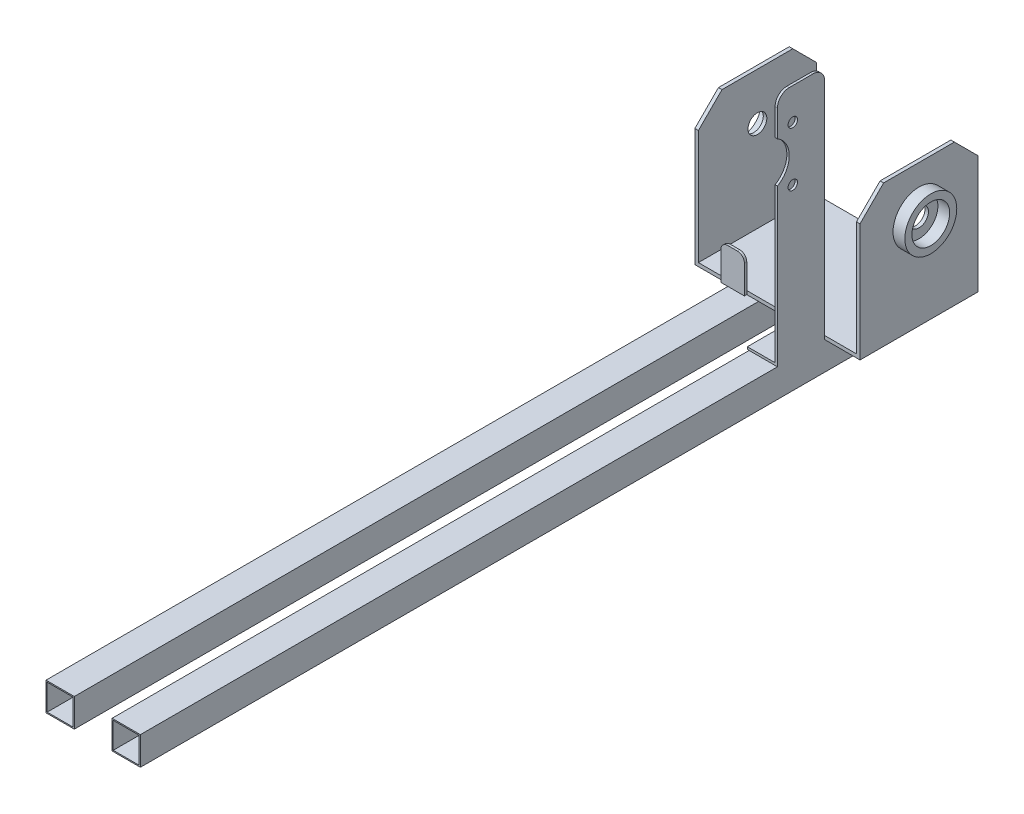
SolidWorks part; units mm, degrees
ref_plane "Front Plane" through (0, 0, 0) normal (0, 0, 1) x (1, 0, 0)
ref_plane "Top Plane" through (0, 0, 0) normal (0, 1, 0) x (1, 0, 0)
ref_plane "Right Plane" through (0, 0, 0) normal (1, 0, 0) x (0, 0, -1)
sketch "Sketch1" plane through (0, 0, 0) normal (0, 0, 1) x (1, 0, 0)
  line L0 (-65.8165, 13.0444) -> (-65.8165, -46.9556)
  line L1 (-65.8165, -46.9556) -> (4.1835, -46.9556)
  line L2 (4.1835, -46.9556) -> (4.1835, 13.0444)
  line L3 (-64.3165, 13.0444) -> (-64.3165, -45.4556)
  line L4 (-64.3165, -45.4556) -> (2.6835, -45.4556)
  line L5 (2.6835, -45.4556) -> (2.6835, 13.0444)
  line L6 (-65.8165, 13.0444) -> (-64.3165, 13.0444)
  line L8 (2.6835, 13.0444) -> (4.1835, 13.0444)
  dimension "D1" = 60
  dimension "D2" = 60
  dimension "D3" = 70
  dimension "D4" = 1.5
extrude "Boss-Extrude1" add sketch "Sketch1" along normal blind 50 contours L0 L1 L2 L8 L5 L4 L3 L6
chamfer "Chamfer1" distance 10 angle 45 4 edges at (-65.0665, 13.0444, 0) (-65.0665, 13.0444, 50) (3.4335, 13.0444, 50) (3.4335, 13.0444, 0)
sketch "Sketch2" plane through (4.1835, 0, 0) normal (1, 0, 0) x (0, 0, -1)
  line L1 (-50, -46.9556) -> (0, -46.9556) construction
  circle A0 centre (-25, -6.9556) radius 4
  dimension "D1" = 40
extrude "Cut-Extrude1" cut sketch "Sketch2" against normal blind 80
sketch "Sketch3" plane through (4.1835, 0, 0) normal (1, 0, 0) x (0, 0, -1)
  circle A0 centre (-25, -6.9556) radius 11
  circle A1 centre (-25, -6.9556) radius 8
  dimension "D1" = 22
  dimension "D2" = 16
extrude "Boss-Extrude2" add sketch "Sketch3" along normal blind 5 contours A0 | A1
ref_plane "Plane1" through (-30.8165, 0, 0) normal (-1, 0, 0) x (0, 0, 1)
mirror "Mirror1" about plane through (-30.8165, 0, 0) normal (-1, 0, 0) of "Boss-Extrude2"
sketch "Sketch4" plane through (0, 0, 0) normal (0, 0, -1) x (-1, 0, 0)
  line L0 (11.3165, -47.4556) -> (11.3165, -58.4556)
  line L1 (65.8165, -46.9556) -> (-4.1835, -46.9556) construction
  line L2 (11.3165, -58.4556) -> (22.3165, -58.4556)
  line L3 (10.8165, -46.9556) -> (22.8165, -46.9556)
  line L4 (10.8165, -46.9556) -> (10.8165, -58.9556)
  line L5 (10.8165, -58.9556) -> (22.8165, -58.9556)
  line L6 (22.8165, -46.9556) -> (22.8165, -58.9556)
  line L7 (22.3165, -47.4556) -> (22.3165, -58.4556)
  line L8 (11.3165, -47.4556) -> (22.3165, -47.4556)
  dimension "D1" = 12
  dimension "D2" = 12
  dimension "D3" = 0.5
extrude "Boss-Extrude3" add sketch "Sketch4" against normal blind 340
mirror "Mirror2" about plane through (-30.8165, 0, 0) normal (-1, 0, 0) of "Boss-Extrude3"
sketch "Sketch5" plane through (0, 0, 0) normal (0, 0, -1) x (-1, 0, 0)
  line L1 (10.8165, -58.9556) -> (50.8165, -58.9556)
  line L2 (10.8165, -58.9556) -> (10.8165, -46.9556)
  line L3 (10.8165, -46.9556) -> (50.8165, -46.9556)
  line L4 (50.8165, -58.9556) -> (50.8165, -46.9556)
extrude "Boss-Extrude4" add sketch "Sketch5" against normal blind 12
sketch "Sketch6" plane through (-10.8165, 0, 0) normal (1, 0, 0) x (0, 0, -1)
  line L5 (-11.5, -58.4556) -> (-11.5, -47.4556)
  line L6 (-0.5, -47.4556) -> (-11.5, -47.4556)
  line L7 (-0.5, -58.4556) -> (-0.5, -47.4556)
  line L8 (-0.5, -58.4556) -> (-11.5, -58.4556)
extrude "Cut-Extrude2" cut sketch "Sketch6" against normal blind 67
sketch "Sketch7" plane through (0, 0, 50) normal (0, 0, 1) x (1, 0, 0)
  line L0 (-23.5702, -45.9556) -> (-11.8165, -45.9556)
  line L1 (-11.8165, -45.9556) -> (-11.8165, 53.0444)
  line L2 (-38.8165, -46.9556) -> (-22.8165, -46.9556) construction
  line L3 (-23.5702, -46.9556) -> (-10.8165, -46.9556)
  line L4 (-10.8165, -46.9556) -> (-10.8165, 53.0444)
  line L5 (-23.5702, -45.9556) -> (-23.5702, -46.9556)
  line L6 (-11.8165, 53.0444) -> (-10.8165, 53.0444)
  dimension "D2" = 100
  dimension "D1" = 1
extrude "Boss-Extrude5" add sketch "Sketch7" along normal blind 20
fillet "Fillet1" radius 5 2 edges at (-11.3165, 53.0444, 70) (-11.3165, 53.0444, 50)
sketch "Sketch8" plane through (-10.8165, 0, 0) normal (1, 0, 0) x (0, 0, -1)
  line L0 (-70, -46.9556) -> (-70, 28.0444)
  line L1 (-70, -46.9556) -> (-70, 48.0444) construction
  line L2 (-70, 28.0444) -> (-75, 28.0444)
  line L8 (-86.5, 16.5444) -> (-63.5, 39.5444) construction
  line L9 (-86.5, 39.5444) -> (-63.5, 16.5444) construction
  circle A0 centre (-75, 28.0444) radius 10
  circle A1 centre (-63.5, 39.5444) radius 2
  circle A2 centre (-63.5, 16.5444) radius 2
  line M7 (-70, 48.0444) -> (-70, -46.9556)
  dimension "D3" = 23
  dimension "D1" = 75
  dimension "D2" = 5
  dimension "D4" = 23
extrude "Cut-Extrude3" cut sketch "Sketch8" against normal blind 20 contours A1 | A0 M7 | A2
sketch "Sketch9" plane through (-50.8165, 0, 0) normal (-1, 0, 0) x (0, 0, 1)
  line L0 (70, -46.9556) -> (50, -46.9556) construction
  line L1 (50, -46.9556) -> (51, -46.9556)
  line L2 (50, -46.9556) -> (50, -31.9556)
  line L3 (50, -31.9556) -> (51, -31.9556)
  line L4 (51, -46.9556) -> (51, -31.9556)
  line L5 (50, 3.0444) -> (50, -46.9556) construction
  dimension "D1" = 15
  dimension "D2" = 1
  dimension "D3" = 0
extrude "Boss-Extrude6" add sketch "Sketch9" along normal blind 3 and the other way blind 7
fillet "Fillet2" radius 3 2 edges at (-53.8165, -31.9556, 50.5) (-43.8165, -31.9556, 50.5)
